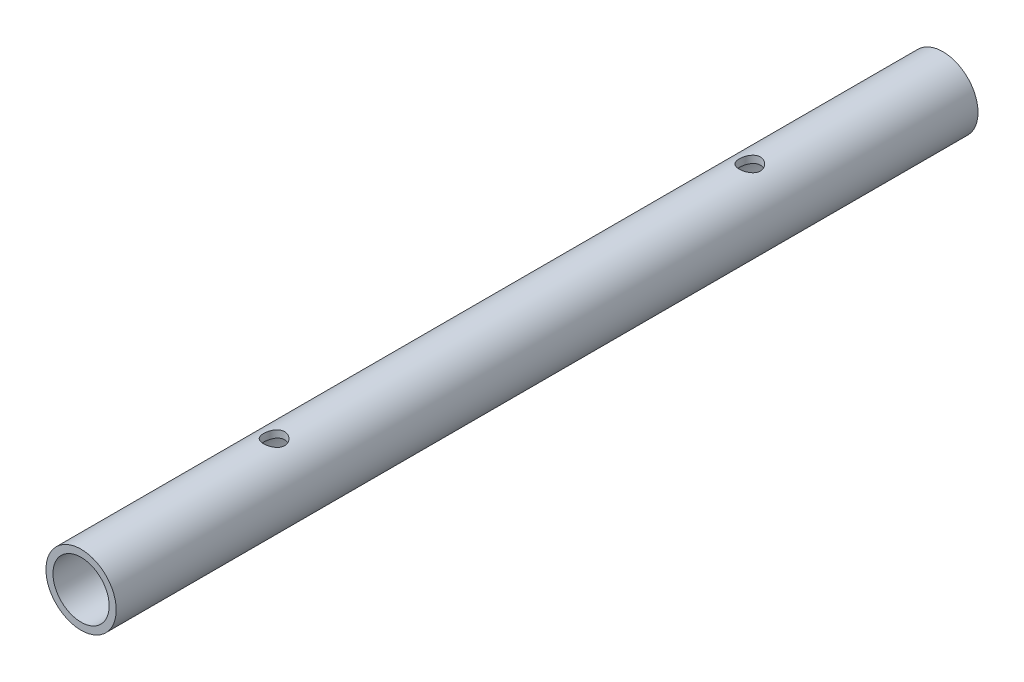
SolidWorks part; units mm, degrees
ref_plane "Plan de face" through (0, 0, 0) normal (0, 0, 1) x (1, 0, 0)
ref_plane "Plan de dessus" through (0, 0, 0) normal (0, 1, 0) x (1, 0, 0)
ref_plane "Plan de droite" through (0, 0, 0) normal (1, 0, 0) x (0, 0, -1)
sketch "Sketch1" plane through (0, 0, 0) normal (0, 0, 1) x (1, 0, 0)
  circle A0 centre (0, 0) radius 5
extrude "Boss-Extrude1" add sketch "Sketch1" along normal blind 122.638
sketch "Sketch2" plane through (0, 0, 122.638) normal (0, 0, 1) x (1, 0, 0)
  circle A0 centre (0, 0) radius 4
extrude "Cut-Extrude1" cut sketch "Sketch2" against normal up to next
sketch "Sketch5" plane through (0, 0, 0) normal (0, 1, 0) x (1, 0, 0)
  circle A0 centre (0, -27.471) radius 1.5
  circle A1 centre (0, -95.167) radius 1.5
  dimension "D1" = 27.471
  dimension "D2" = 95.167
extrude "Cut-Extrude2" cut sketch "Sketch5" against normal through all and the other way through all
